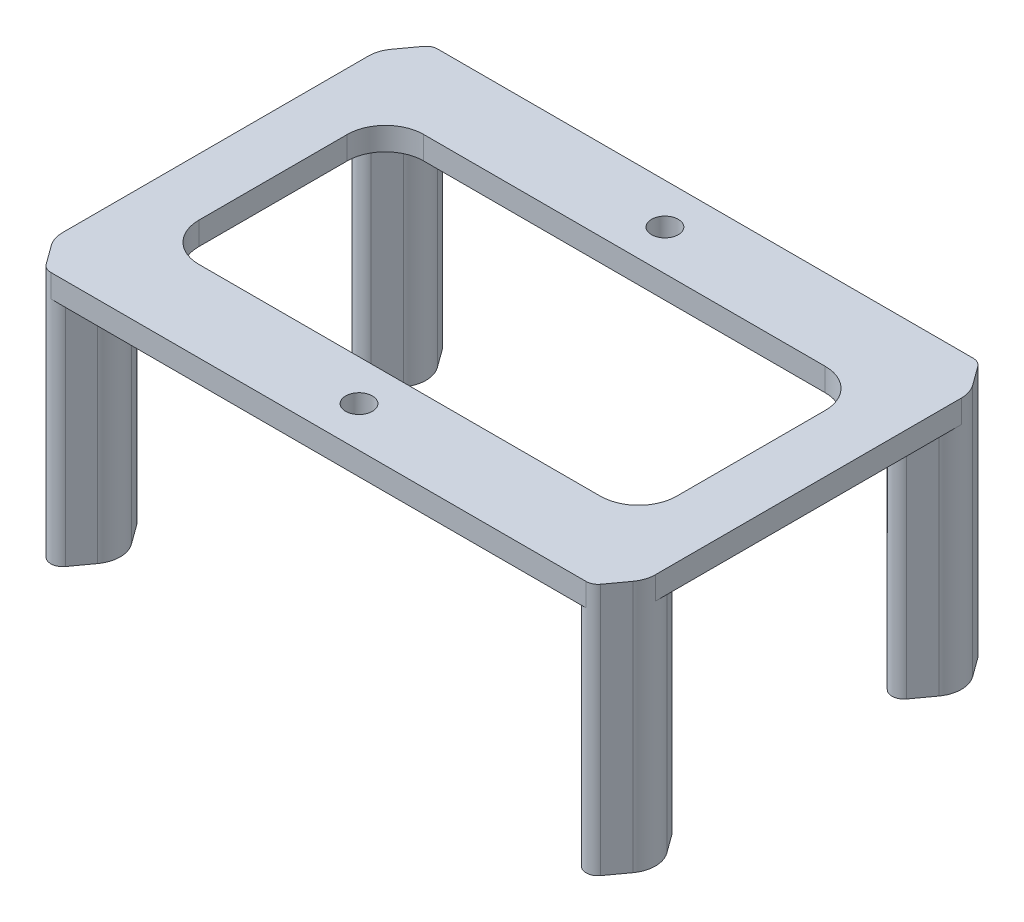
SolidWorks part; units mm, degrees
ref_plane "Front Plane" through (0, 0, 0) normal (0, 0, 1) x (1, 0, 0)
ref_plane "Top Plane" through (0, 0, 0) normal (0, 1, 0) x (1, 0, 0)
ref_plane "Right Plane" through (0, 0, 0) normal (1, 0, 0) x (0, 0, -1)
sketch "Sketch1" plane through (0, 0, 0) normal (0, 1, 0) x (1, 0, 0)
  line L0 (-1.25, 4.6585) -> (-3.0334, 2.2047)
  line L1 (1.25, 4.6585) -> (3.0334, 2.2047)
  line L2 (-3.0334, -2.2047) -> (-1.25, -4.6585)
  line L3 (1.25, -4.6585) -> (3.0334, -2.2047)
  line L4 (68.75, 4.6585) -> (66.9666, 2.2047)
  line L5 (71.25, 4.6585) -> (73.0334, 2.2047)
  line L6 (66.9666, -2.2047) -> (68.75, -4.6585)
  line L7 (71.25, -4.6585) -> (73.0334, -2.2047)
  line L8 (68.75, -35.3415) -> (66.9666, -37.7953)
  line L9 (71.25, -35.3415) -> (73.0334, -37.7953)
  line L10 (66.9666, -42.2047) -> (68.75, -44.6585)
  line L11 (71.25, -44.6585) -> (73.0334, -42.2047)
  line L12 (-1.25, -35.3415) -> (-3.0334, -37.7953)
  line L13 (1.25, -35.3415) -> (3.0334, -37.7953)
  line L14 (-3.0334, -42.2047) -> (-1.25, -44.6585)
  line L15 (1.25, -44.6585) -> (3.0334, -42.2047)
  circle A0 centre (0, 0) radius 1.6
  circle A1 centre (70, 0) radius 1.6
  circle A2 centre (0, -40) radius 1.6
  circle A3 centre (70, -40) radius 1.6
  arc A4 (3.0334, -2.2047) -> (3.0334, 2.2047) centre (0, 0) ccw
  arc A5 (1.25, 4.6585) -> (-1.25, 4.6585) centre (0, 3.75) ccw
  arc A6 (-1.25, -4.6585) -> (1.25, -4.6585) centre (0, -3.75) ccw
  arc A7 (-3.0334, 2.2047) -> (-3.0334, -2.2047) centre (0, 0) ccw
  arc A8 (71.25, 4.6585) -> (68.75, 4.6585) centre (70, 3.75) ccw
  arc A9 (68.75, -4.6585) -> (71.25, -4.6585) centre (70, -3.75) ccw
  arc A10 (73.0334, -2.2047) -> (73.0334, 2.2047) centre (70, 0) ccw
  arc A11 (66.9666, 2.2047) -> (66.9666, -2.2047) centre (70, 0) ccw
  arc A12 (71.25, -35.3415) -> (68.75, -35.3415) centre (70, -36.25) ccw
  arc A13 (68.75, -44.6585) -> (71.25, -44.6585) centre (70, -43.75) ccw
  arc A14 (73.0334, -42.2047) -> (73.0334, -37.7953) centre (70, -40) ccw
  arc A15 (66.9666, -37.7953) -> (66.9666, -42.2047) centre (70, -40) ccw
  arc A16 (1.25, -35.3415) -> (-1.25, -35.3415) centre (0, -36.25) ccw
  arc A17 (-1.25, -44.6585) -> (1.25, -44.6585) centre (0, -43.75) ccw
  arc A18 (3.0334, -42.2047) -> (3.0334, -37.7953) centre (0, -40) ccw
  arc A19 (-3.0334, -37.7953) -> (-3.0334, -42.2047) centre (0, -40) ccw
  point P10 (1.1438, 4.639)
  dimension "D1" = 3.2
  dimension "D4" = 7.5
  dimension "D2" = 70
  dimension "D3" = 40
  dimension "D7" = 2.5
  dimension "D5" = 2
  dimension "D6" = 2
extrude "Boss-Extrude1" add sketch "Sketch1" along normal blind 30
sketch "Sketch2" plane through (0, 30, 0) normal (0, 1, 0) x (1, 0, 0)
  line L0 (-3.75, 0) -> (-3.75, -40)
  line L1 (73.75, 0) -> (73.75, -40)
  line L40 (-1.25, 4.6585) -> (-3.0334, 2.2047)
  line L41 (-3.0334, -2.2047) -> (-1.25, -4.6585)
  line L42 (1.25, -4.6585) -> (3.0334, -2.2047)
  line L43 (3.0334, 2.2047) -> (1.25, 4.6585)
  line L44 (-1.25, 4.6585) -> (-3.0334, 2.2047)
  line L52 (-1.25, -35.3415) -> (-3.0334, -37.7953)
  line L53 (-3.0334, -42.2047) -> (-1.25, -44.6585)
  line L54 (1.25, -44.6585) -> (3.0334, -42.2047)
  line L55 (3.0334, -37.7953) -> (1.25, -35.3415)
  line L57 (-3.0334, -42.2047) -> (-1.25, -44.6585)
  line L64 (68.75, -35.3415) -> (66.9666, -37.7953)
  line L65 (66.9666, -42.2047) -> (68.75, -44.6585)
  line L66 (71.25, -44.6585) -> (73.0334, -42.2047)
  line L67 (73.0334, -37.7953) -> (71.25, -35.3415)
  line L70 (71.25, -44.6585) -> (73.0334, -42.2047)
  line L72 (0, 5.2953) -> (70, 5.2953)
  line L73 (0, -45.2953) -> (70, -45.2953)
  line L74 (8.75, -34.7047) -> (61.25, -34.7047)
  line L75 (8.75, -5.2953) -> (61.25, -5.2953)
  line L76 (68.75, 4.6585) -> (66.9666, 2.2047)
  line L77 (66.9666, -2.2047) -> (68.75, -4.6585)
  line L78 (71.25, -4.6585) -> (73.0334, -2.2047)
  line L79 (73.0334, 2.2047) -> (71.25, 4.6585)
  line L83 (73.0334, 2.2047) -> (71.25, 4.6585)
  line L84 (3.75, -10.2953) -> (3.75, -29.7047)
  line L85 (66.25, -10.2953) -> (66.25, -29.7047)
  arc A0 (-3.0334, 2.2047) -> (-3.0334, -2.2047) centre (0, 0) ccw construction
  arc A1 (-3.0334, -37.7953) -> (-3.0334, -42.2047) centre (0, -40) ccw construction
  arc A2 (73.0334, -2.2047) -> (73.0334, 2.2047) centre (70, 0) ccw construction
  arc A3 (73.0334, -42.2047) -> (73.0334, -37.7953) centre (70, -40) ccw construction
  arc A72 (1.25, 4.6585) -> (-1.25, 4.6585) centre (0, 3.75) ccw
  arc A73 (-3.0334, 2.2047) -> (-3.0334, -2.2047) centre (0, 0) ccw
  arc A74 (-1.25, -4.6585) -> (1.25, -4.6585) centre (0, -3.75) ccw
  arc A75 (3.0334, -2.2047) -> (3.0334, 2.2047) centre (0, 0) ccw
  arc A76 (0, 5.2953) -> (-1.25, 4.6585) centre (0, 3.75) ccw
  arc A77 (-3.0334, 2.2047) -> (-3.75, 0) centre (0, 0) ccw
  arc A84 (1.25, -35.3415) -> (-1.25, -35.3415) centre (0, -36.25) ccw
  arc A85 (-3.0334, -37.7953) -> (-3.0334, -42.2047) centre (0, -40) ccw
  arc A86 (-1.25, -44.6585) -> (1.25, -44.6585) centre (0, -43.75) ccw
  arc A87 (3.0334, -42.2047) -> (3.0334, -37.7953) centre (0, -40) ccw
  arc A89 (-3.75, -40) -> (-3.0334, -42.2047) centre (0, -40) ccw
  arc A90 (-1.25, -44.6585) -> (0, -45.2953) centre (0, -43.75) ccw
  arc A96 (71.25, -35.3415) -> (68.75, -35.3415) centre (70, -36.25) ccw
  arc A97 (66.9666, -37.7953) -> (66.9666, -42.2047) centre (70, -40) ccw
  arc A98 (68.75, -44.6585) -> (71.25, -44.6585) centre (70, -43.75) ccw
  arc A99 (73.0334, -42.2047) -> (73.0334, -37.7953) centre (70, -40) ccw
  arc A102 (70, -45.2953) -> (71.25, -44.6585) centre (70, -43.75) ccw
  arc A103 (73.0334, -42.2047) -> (73.75, -40) centre (70, -40) ccw
  arc A104 (61.25, -34.7047) -> (66.25, -29.7047) centre (61.25, -29.7047) ccw
  arc A105 (3.75, -29.7047) -> (8.75, -34.7047) centre (8.75, -29.7047) ccw
  arc A106 (3.75, -10.2953) -> (8.75, -5.2953) centre (8.75, -10.2953) cw
  arc A107 (61.25, -5.2953) -> (66.25, -10.2953) centre (61.25, -10.2953) cw
  arc A108 (71.25, 4.6585) -> (68.75, 4.6585) centre (70, 3.75) ccw
  arc A109 (66.9666, 2.2047) -> (66.9666, -2.2047) centre (70, 0) ccw
  arc A110 (68.75, -4.6585) -> (71.25, -4.6585) centre (70, -3.75) ccw
  arc A111 (73.0334, -2.2047) -> (73.0334, 2.2047) centre (70, 0) ccw
  arc A112 (71.25, 4.6585) -> (70, 5.2953) centre (70, 3.75) ccw
  arc A115 (73.75, 0) -> (73.0334, 2.2047) centre (70, 0) ccw
  dimension "D5" = 5
  dimension "D1" = 0
  dimension "D2" = 0
  dimension "D3" = 0
  dimension "D4" = 0
extrude "Boss-Extrude2" add sketch "Sketch2" along normal blind 3
sketch "Sketch3" plane through (0, 33, 0) normal (0, 1, 0) x (1, 0, 0)
  line L0 (61.25, -5.2953) -> (8.75, -5.2953) construction
  line L1 (70, 5.2953) -> (0, 5.2953) construction
  circle A0 centre (35, -0.0047) radius 1.75
  circle A1 centre (35, -40.0047) radius 1.75
  point P4 (35, -5.2953)
  point P5 (0, 0)
  point P8 (0, 0)
  dimension "D1" = 3.5
  dimension "D2" = 3.5
  dimension "D3" = 40
  dimension "D4" = 5.3
extrude "Cut-Extrude1" cut sketch "Sketch3" against normal blind 3
